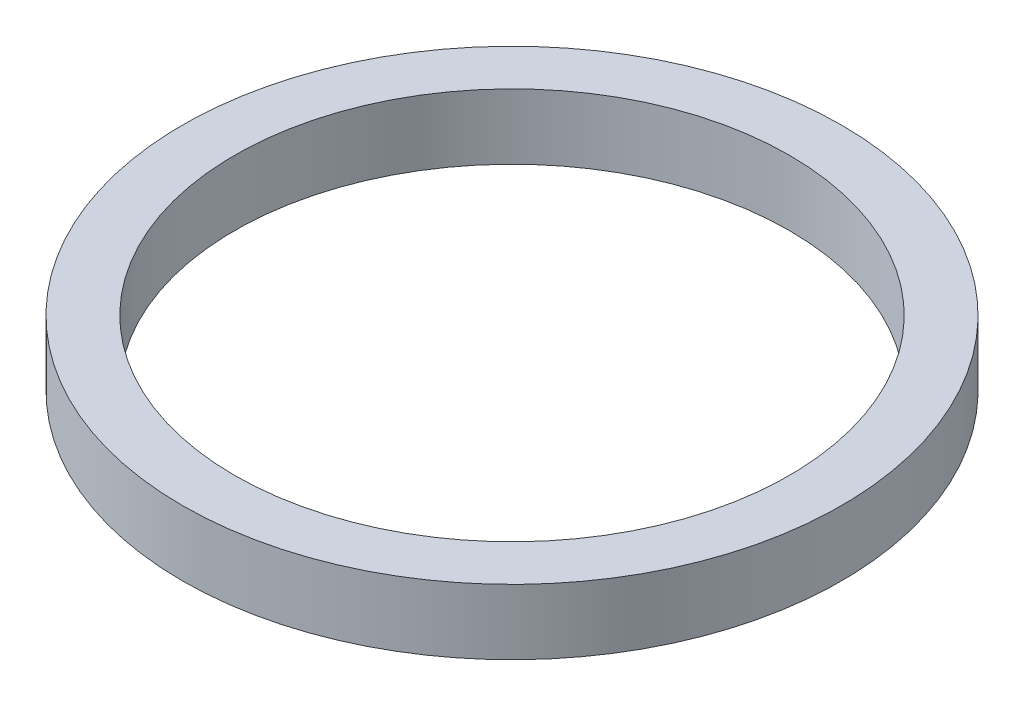
SolidWorks part; units mm, degrees
ref_plane "Alzado" through (0, 0, 0) normal (0, 0, 1) x (1, 0, 0)
ref_plane "Planta" through (0, 0, 0) normal (0, 1, 0) x (1, 0, 0)
ref_plane "Vista lateral" through (0, 0, 0) normal (1, 0, 0) x (0, 0, -1)
sketch "Croquis1" plane through (0, 0, 0) normal (0, 1, 0) x (1, 0, 0)
  circle A0 centre (0, 0) radius 21.25
  circle A1 centre (0, 0) radius 25.25
  dimension "D1" = 42.5
  dimension "D2" = 4
extrude "Saliente-Extruir1" add sketch "Croquis1" along normal blind 5
